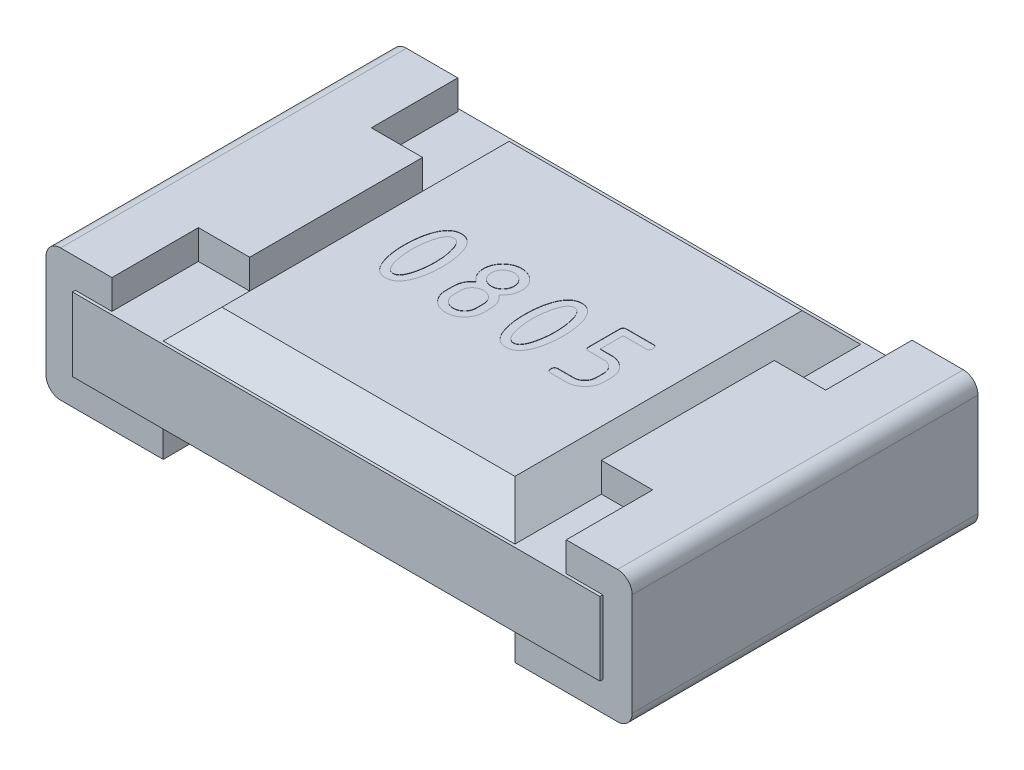
SolidWorks part; units mm, degrees
ref_plane "Front" through (0, 0, 0) normal (0, 0, 1) x (1, 0, 0)
ref_plane "Top" through (0, 0, 0) normal (0, 1, 0) x (1, 0, 0)
ref_plane "Right" through (0, 0, 0) normal (1, 0, 0) x (0, 0, -1)
sketch "Sketch1" plane through (0, 0, 0) normal (0, 1, 0) x (1, 0, 0)
  line L1 (-0.9, -0.6) -> (0.9, -0.6)
  line L2 (-0.9, -0.6) -> (-0.9, 0.6)
  line L3 (-0.9, 0.6) -> (0.9, 0.6)
  line L4 (0.9, -0.6) -> (0.9, 0.6)
  line L5 (-0.9, -0.6) -> (0.9, 0.6) construction
  line L6 (-0.9, 0.6) -> (0.9, -0.6) construction
  point P0 (0, 0)
  dimension "D1" = 1.8
  dimension "D2" = 1.2
extrude "Boss-Extrude1" add sketch "Sketch1" along normal mid plane 0.25
sketch "Sketch2" plane through (0, 0, 0) normal (0, 1, 0) x (1, 0, 0)
  line L0 (-1, 0.59) -> (-0.6, 0.59)
  line L1 (0.9, 0.6) -> (-0.9, 0.6) construction
  line L2 (-0.6, 0.59) -> (-0.6, -0.59)
  line L8 (-0.6, -0.59) -> (-1, -0.59)
  line L9 (-1, -0.59) -> (-1, 0.59)
  line L11 (0, 0) -> (0, 0.6) construction
  line L20 (0, 0) -> (-0.6, 0) construction
  line L21 (-0.6, 0) -> (-1, 0) construction
  line L37 (1, -0.59) -> (1, 0.59)
  line L38 (0.6, -0.59) -> (1, -0.59)
  line L39 (0.6, 0.59) -> (0.6, -0.59)
  line L40 (1, 0.59) -> (0.6, 0.59)
  dimension "D1" = 2
  dimension "D2" = 1.2
  dimension "D5" = 1.18
extrude "Boss-Extrude2" add sketch "Sketch2" along normal mid plane 0.45
fillet "Fillet1" radius 0.05 4 edges at (-1, -0.225, 0) (-1, 0.225, 0) (1, -0.225, 0) (1, 0.225, 0)
sketch "Sketch6" plane through (0, 0.225, 0) normal (0, 1, 0) x (1, 0, 0)
  line L0 (-0.6, 0.59) -> (-0.95, 0.59) construction
  line L1 (-0.775, 0.59) -> (0.775, 0.59)
  line L2 (-0.775, 0.59) -> (-0.775, 0.295)
  line L3 (-0.775, 0.295) -> (0.775, 0.295)
  line L4 (0.775, 0.59) -> (0.775, 0.295)
  line L5 (-0.95, -0.59) -> (-0.6, -0.59) construction
  line L6 (-0.775, -0.59) -> (0.775, -0.59)
  line L7 (-0.775, -0.59) -> (-0.775, -0.295)
  line L8 (-0.775, -0.295) -> (0.775, -0.295)
  line L9 (0.775, -0.59) -> (0.775, -0.295)
  line L10 (0.6, -0.59) -> (0.95, -0.59) construction
  line L11 (-0.775, 0.295) -> (-0.775, 0) construction
  line L12 (-0.775, 0) -> (-0.775, -0.295) construction
extrude "Cut-Extrude2" cut sketch "Sketch6" against normal up to surface (0.1 mm away) up to face at (0, 0.125, 0)
sketch "Sketch4" plane through (0, 0.125, 0) normal (0, 1, 0) x (1, 0, 0)
  line L0 (0.6, 0.295) -> (0.6, -0.295) construction
  line L5 (-0.775, 0.59) -> (-0.9, 0.59) construction
  line L6 (-0.6, -0.59) -> (0.6, -0.59)
  line L8 (-0.6, -0.59) -> (-0.6, 0.59)
  line L9 (-0.6, 0.59) -> (0.6, 0.59)
  line L10 (0.6, -0.59) -> (0.6, 0.59)
  line L11 (-0.6, -0.59) -> (0.6, 0.59) construction
  line L12 (-0.6, 0.59) -> (0.6, -0.59) construction
  point P0 (0, 0)
extrude "Boss-Extrude3" add sketch "Sketch4" along normal up to surface (0.1 mm away) draft 45
sketch "Sketch5" plane through (0, 0.225, 0) normal (0, 1, 0) x (1, 0, 0)
  line L0 (-0.5, -0.1239) -> (0.5, -0.1239) construction
  line L1 (-0.5, 0.49) -> (-0.5, -0.49) construction
  line L2 (0.5, -0.49) -> (0.5, 0.49) construction
  text T0 "0805" font "@Adobe Fan Heiti Std B" height 0.26
extrude "Cut-Extrude1" cut sketch "Sketch5" against normal blind 0.001
